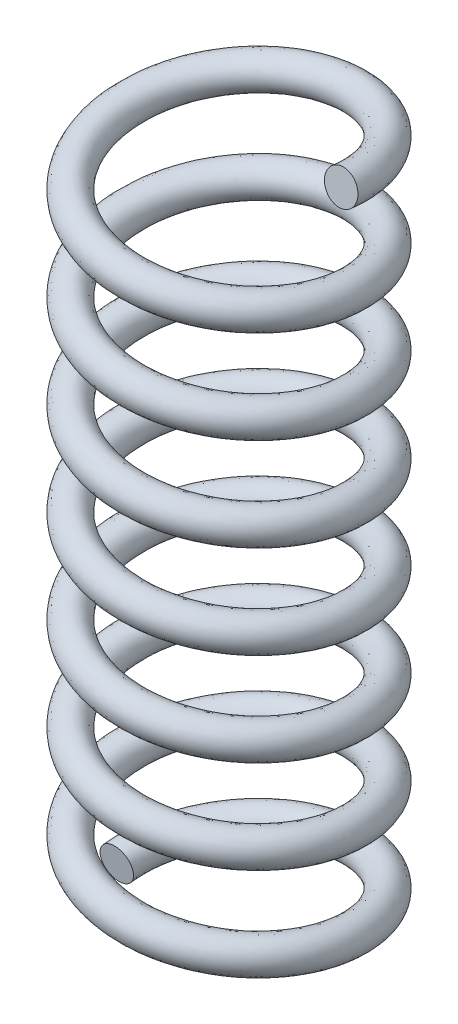
SolidWorks part; units mm, degrees
ref_plane "Front Plane" through (0, 0, 0) normal (0, 0, 1) x (1, 0, 0)
ref_plane "Top Plane" through (0, 0, 0) normal (0, 1, 0) x (1, 0, 0)
ref_plane "Right Plane" through (0, 0, 0) normal (1, 0, 0) x (0, 0, -1)
sketch "Sketch1" plane through (0, 0, 0) normal (0, 1, 0) x (1, 0, 0)
  circle A0 centre (0, 0) radius 3.375
  dimension "D1" = 6.75
curve "Helix/Spiral1" pitch 2.8 height 21 turns 7.5
sweep "Sweep1" add path "Helix/Spiral1" circular profile diameter 1 parameters "D3"=1
